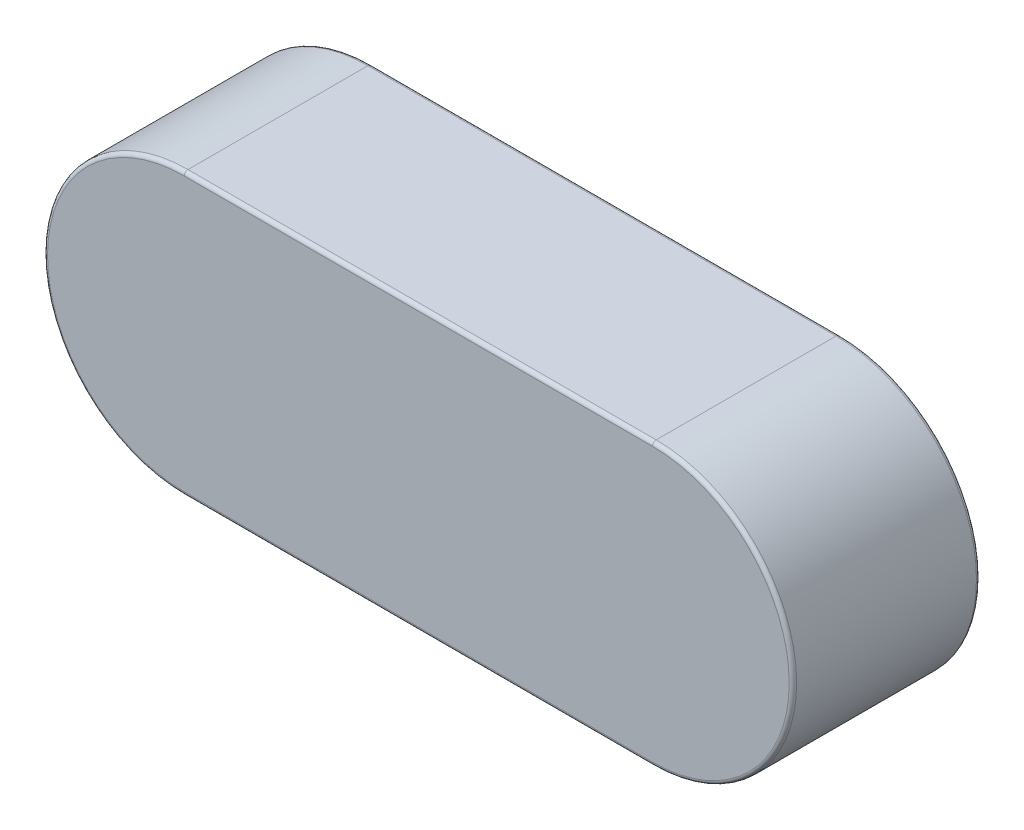
SolidWorks part; units mm, degrees
ref_plane "Спереди" through (0, 0, 0) normal (0, 0, 1) x (1, 0, 0)
ref_plane "Сверху" through (0, 0, 0) normal (0, 1, 0) x (1, 0, 0)
ref_plane "Справа" through (0, 0, 0) normal (1, 0, 0) x (0, 0, -1)
sketch "Эскиз1" plane through (0, 0, 0) normal (0, 0, 1) x (1, 0, 0)
  line L0 (0, 0) -> (20, 0) construction
  line L1 (0, 6) -> (20, 6)
  line L2 (0, -6) -> (20, -6)
  arc A0 (0, 6) -> (0, -6) centre (0, 0) ccw
  arc A1 (20, -6) -> (20, 6) centre (20, 0) ccw
  point P3 (10, 0)
  point P8 (0, 0)
  point P9 (0, 0)
  dimension "D1" = 20
  dimension "D2" = 12
extrude "Бобышка-Вытянуть1" add sketch "Эскиз1" along normal blind 8
fillet "Скругление1" radius 0.16 8 edges at (10, 6, 8) (26, 0, 8) (10, -6, 8) (-6, 0, 8) (10, -6, 0) (26, 0, 0) (10, 6, 0) (-6, 0, 0)
